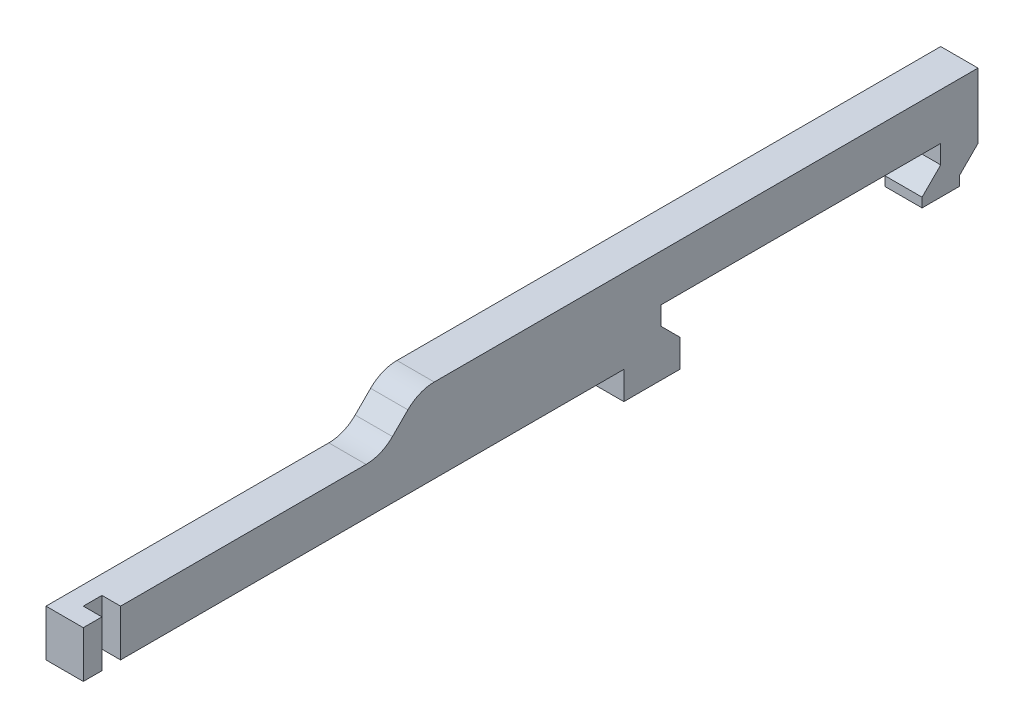
SolidWorks part; units mm, degrees
ref_plane "Спереди" through (0, 0, 0) normal (0, 0, 1) x (1, 0, 0)
ref_plane "Сверху" through (0, 0, 0) normal (0, 1, 0) x (1, 0, 0)
ref_plane "Справа" through (0, 0, 0) normal (1, 0, 0) x (0, 0, -1)
sketch "Эскиз1" plane through (0, 0, 0) normal (1, 0, 0) x (0, 0, -1)
  line L0 (16, 2.5) -> (18, 4.5)
  line L1 (0, 0) -> (16, 0)
  line L2 (0, 0) -> (0, 2.5)
  line L3 (0, 2.5) -> (16, 2.5)
  line L4 (16, 0) -> (16, 2.5)
  line L5 (18, 4.5) -> (18, 2.5) construction
  line L6 (18, 2.5) -> (16, 2.5) construction
  line L7 (18, 4.5) -> (29, 4.5)
  line L8 (16, 0) -> (29, 0)
  line L9 (29, 0) -> (29, -1.5)
  line L10 (29, -1.5) -> (32, -1.5)
  line L11 (32, -1.5) -> (32, 0)
  line L12 (32, 0) -> (31, 1)
  line L13 (31, 1) -> (31, 2)
  line L14 (31, 2) -> (46, 2)
  line L15 (32, 0) -> (31, 0) construction
  line L16 (31, 0) -> (31, 1) construction
  line L17 (38.5, 2) -> (38.5, 1) construction
  line L18 (45, 0) -> (46, 1)
  line L19 (46, 1) -> (46, 2)
  line L20 (45, 0) -> (45, -0.5)
  line L21 (45, -0.5) -> (47, -0.5)
  line L22 (47, -0.5) -> (47, 0)
  line L23 (47, 0) -> (48, 1)
  line L24 (48, 1) -> (48, 4.5)
  line L25 (48, 4.5) -> (29, 4.5)
  dimension "D1" = 2.5
  dimension "D2" = 16
  dimension "D3" = 2
  dimension "D4" = 2
  dimension "D5" = 11
  dimension "D6" = 13
  dimension "D7" = 1.5
  dimension "D8" = 3
  dimension "D9" = 1.5
  dimension "D10" = 1
  dimension "D11" = 1
  dimension "D12" = 1
  dimension "D13" = 15
  dimension "D14" = 0.5
  dimension "D15" = 2
extrude "Бобышка-Вытянуть1" add sketch "Эскиз1" along normal blind 2 contours L24 L25 L7 L0 L4 L8 L9 L10 L11 L12 L13 L14 L19 L18 L20 L21 L22 L23 | L1 L4 L3 L2
fillet "Скругление1" radius 2 2 edges at (1, 4.5, -18) (1, 2.5, -16)
sketch "Эскиз2" plane through (0, 2.5, 0) normal (0, 1, 0) x (1, 0, 0)
  line L0 (2, 0) -> (2, 1) construction
  line L1 (2, 0) -> (2, 15.1716) construction
  line L3 (2, 1) -> (1, 1)
  line L4 (2, 1) -> (2, 2)
  line L5 (2, 2) -> (1, 2)
  line L6 (1, 1) -> (1, 2)
  dimension "D1" = 1
  dimension "D2" = 1
  dimension "D3" = 1
extrude "Вырез-Вытянуть1" cut sketch "Эскиз2" against normal through all
